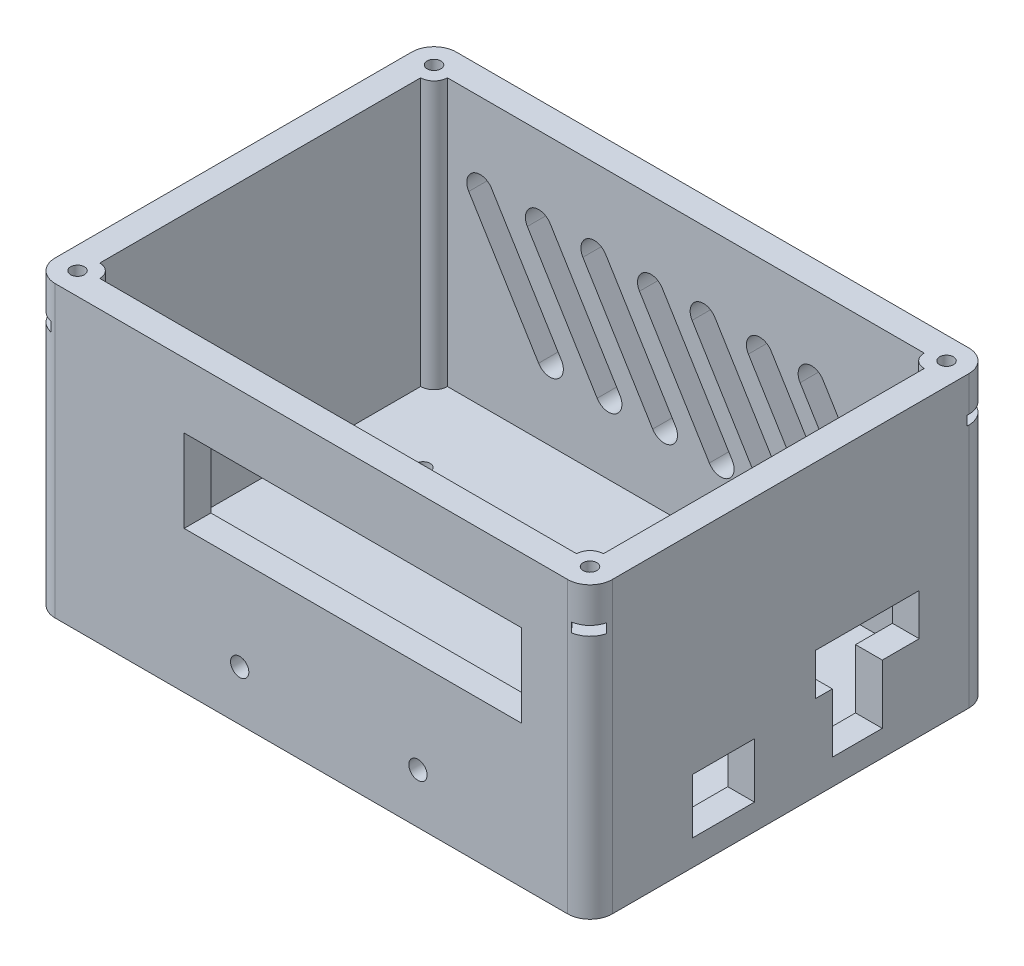
SolidWorks part; units mm, degrees
ref_plane "Front Plane" through (0, 0, 0) normal (0, 0, 1) x (1, 0, 0)
ref_plane "Top Plane" through (0, 0, 0) normal (0, 1, 0) x (1, 0, 0)
ref_plane "Right Plane" through (0, 0, 0) normal (1, 0, 0) x (0, 0, -1)
sketch "Sketch1" plane through (0, 0, 0) normal (0, 1, 0) x (1, 0, 0)
  line L0 (-62.5, 45) -> (62.5, 45)
  line L7 (62.5, 45) -> (62.5, -45)
  line L8 (-62.5, -45) -> (62.5, -45)
  line L9 (-62.5, 45) -> (-62.5, -45)
  point P1 (0, 0)
  point P2 (62.5, 0)
  dimension "D1" = 90
  dimension "D2" = 125
extrude "Boss-Extrude1" add sketch "Sketch1" along normal blind 5
sketch "Sketch2" plane through (0, 5, 0) normal (0, 1, 0) x (1, 0, 0)
  line L8 (-57.5, 40) -> (-57.5, -40)
  line L9 (-57.5, -40) -> (57.5, -40)
  line L10 (57.5, -40) -> (57.5, 40)
  line L11 (57.5, 40) -> (-57.5, 40)
  line L12 (-57.5, 40) -> (-57.5, -40)
  line L13 (-57.5, -40) -> (57.5, -40)
  line L14 (57.5, -40) -> (57.5, 40)
  line L15 (57.5, 40) -> (-57.5, 40)
  dimension "D1" = 5
extrude "Extrude-Thin1" add sketch "Sketch2" along normal blind 60 thin
fillet "Fillet1" radius 5 4 edges at (-62.5, 32.5, -45) (62.5, 32.5, -45) (62.5, 32.5, 45) (-62.5, 32.5, 45)
sketch "Sketch14" plane through (0, 0, 45) normal (0, 0, 1) x (1, 0, 0)
  line L1 (-28.5737, 50.4382) -> (47.1628, 50.4382)
  line L2 (-28.5737, 50.4382) -> (-28.5737, 31.8876)
  line L3 (-28.5737, 31.8876) -> (47.1628, 31.8876)
  line L4 (47.1628, 50.4382) -> (47.1628, 31.8876)
sketch "Sketch17" plane through (0, 0, 39) normal (0, 0, -1) x (-1, 0, 0)
  line L0 (-23.8948, 11.2058) -> (16.1052, 11.2058) construction
  circle A0 centre (-23.8948, 11.2058) radius 2.05
  circle A1 centre (16.1052, 11.2058) radius 2.05
  dimension "D2" = 4.1
  dimension "D3" = 4.1
  dimension "D1" = 40
extrude "Cut-Extrude12" cut sketch "Sketch17" against normal up to next
sketch "Sketch18" plane through (0, 0, 39) normal (0, 0, -1) x (-1, 0, 0)
  line L1 (-21.9213, 7.5472) -> (-19.7396, 11.0856)
  line L2 (-19.7396, 11.0856) -> (-21.7131, 14.7442)
  line L3 (-21.7131, 14.7442) -> (-25.8683, 14.8644)
  line L4 (-25.8683, 14.8644) -> (-28.05, 11.326)
  line L5 (-28.05, 11.326) -> (-26.0765, 7.6674)
  line L6 (-26.0765, 7.6674) -> (-21.9213, 7.5472)
  line L7 (18.0787, 7.5472) -> (20.2604, 11.0856)
  line L8 (20.2604, 11.0856) -> (18.2869, 14.7442)
  line L9 (18.2869, 14.7442) -> (14.1317, 14.8644)
  line L10 (14.1317, 14.8644) -> (11.95, 11.326)
  line L11 (11.95, 11.326) -> (13.9235, 7.6674)
  line L12 (13.9235, 7.6674) -> (18.0787, 7.5472)
  circle A0 centre (-23.8948, 11.2058) radius 3.6 construction
  circle A1 centre (16.1052, 11.2058) radius 3.6 construction
  dimension "D1" = 7.2
  dimension "D2" = 7.2
extrude "Cut-Extrude13" cut sketch "Sketch18" against normal blind 3
extrude "Cut-Extrude15" cut sketch "Sketch14" against normal up to next contours L1 L4 L3 L2
sketch "Sketch20" plane through (0, 5, 0) normal (0, 1, 0) x (1, 0, 0)
  circle A0 centre (-56.5, -39) radius 3
  circle A1 centre (-56.5, 39) radius 3
  circle A2 centre (56.5, 39) radius 3
  circle A3 centre (56.5, -39) radius 3
  dimension "D1" = 6
  dimension "D2" = 6
extrude "Boss-Extrude2" add sketch "Sketch20" along normal blind 60
sketch "Sketch21" plane through (0, 65, 0) normal (0, 1, 0) x (1, 0, 0)
  circle A0 centre (-57.5, -40) radius 1.55
  circle A1 centre (-57.5, 40) radius 1.55
  circle A2 centre (57.5, 40) radius 1.55
  circle A3 centre (57.5, -40) radius 1.55
  dimension "D1" = 3.1
extrude "Cut-Extrude16" cut sketch "Sketch21" against normal blind 15
ref_plane "Plane3" through (0, 55, 0) normal (0, 1, 0) x (1, 0, 0)
sketch "Sketch22" plane through (0, 55, 0) normal (0, 1, 0) x (1, 0, 0)
  line L0 (-56.8583, 43.1688) -> (-60.3698, 46.2698)
  line L1 (-60.5651, 38.9713) -> (-58.1417, 36.8312)
  line L2 (-58.1417, 36.8312) -> (-55.0765, 37.8599)
  line L3 (-55.0765, 37.8599) -> (-54.4349, 41.0287)
  line L4 (-54.4349, 41.0287) -> (-56.8583, 43.1688)
  line L7 (57.5, 43.2332) -> (54.7, 41.6166)
  line L8 (54.7, 41.6166) -> (54.7, 38.3834)
  line L9 (54.7, 38.3834) -> (57.5, 36.7668)
  line L10 (57.5, 36.7668) -> (60.3, 38.3834)
  line L15 (60.6503, -39.2728) -> (58.4454, -36.9082)
  line L16 (58.4454, -36.9082) -> (55.2951, -37.6353)
  line L17 (55.2951, -37.6353) -> (54.3497, -40.7272)
  line L18 (54.3497, -40.7272) -> (56.5546, -43.0918)
  line L19 (-54.3782, -40.8414) -> (-55.2104, -37.7172)
  line L20 (-55.2104, -37.7172) -> (-58.3322, -36.8758)
  line L21 (-58.3322, -36.8758) -> (-60.6218, -39.1586)
  line L24 (-56.6678, -43.1242) -> (-54.3782, -40.8414)
  line L25 (-60.3698, 46.2698) -> (-64.0167, 42.1401)
  line L26 (-64.0167, 42.1401) -> (-60.5651, 38.9713)
  line L27 (57.5, 43.2332) -> (61.574, 45.5853)
  line L28 (61.574, 45.5853) -> (64.3757, 40.7325)
  line L29 (64.3757, 40.7325) -> (60.3, 38.3834)
  line L30 (56.5546, -43.0918) -> (59.7049, -46.4705)
  line L31 (59.7049, -46.4705) -> (63.7747, -42.6756)
  line L32 (63.7747, -42.6756) -> (60.6503, -39.2728)
  line L33 (-60.6218, -39.1586) -> (-64.278, -42.804)
  line L34 (-64.278, -42.804) -> (-60.3698, -46.7238)
  line L36 (-56.6678, -43.1242) -> (-60.3698, -46.7238)
  line L38 (-60.2057, -40.7207) -> (-59.7896, -42.2828) [skipped]
  line L39 (-59.7896, -42.2828) -> (-58.2287, -42.7035) [skipped]
  line L40 (58.1297, -42.7283) -> (59.7049, -42.3647) [skipped]
  line L41 (60.1776, -40.8188) -> (60.6503, -39.2728) [skipped]
  line L42 (60.3, 41.6166) -> (58.9, 42.4249) [skipped]
  line L43 (60.3, 38.3834) -> (60.3, 40) [skipped]
  line L44 (-56.8583, 43.1688) -> (-58.3909, 42.6545) [skipped]
  line L45 (-60.2443, 40.5557) -> (-60.5651, 38.9713) [skipped]
  circle A0 centre (-57.5, 40) radius 2.8 construction
  circle A1 centre (57.5, 40) radius 2.8 construction
  circle A2 centre (57.5, -40) radius 2.8 construction
  circle A3 centre (-57.5, -40) radius 2.8 construction
  dimension "D2" = 5.6
  dimension "D3" = 5.6
  dimension "D4" = 5.6
extrude "Cut-Extrude17" cut sketch "Sketch22" along normal blind 2.1
sketch "Sketch23" plane through (0, 0, -45) normal (0, 0, -1) x (-1, 0, 0)
  line L0 (-38.1886, 46.8799) -> (46.1005, 46.8799) construction
  line L1 (-28.2059, 46.8799) -> (-43.8731, 21.3293) construction
  line L2 (-38.1886, 21.3293) -> (46.1005, 21.3293) construction
  line L3 (-25.6484, 45.3116) -> (-41.3157, 19.7611)
  line L4 (-30.7633, 48.4481) -> (-46.4306, 22.8976)
  line L5 (-16.5954, 46.643) -> (-32.2626, 21.0925) construction
  line L10 (-14.0379, 45.0748) -> (-29.7052, 19.5243)
  line L15 (-19.1528, 48.2112) -> (-34.8201, 22.6607)
  line L18 (-3.967, 46.8799) -> (-19.6342, 21.3293) construction
  line L21 (-1.4095, 45.3116) -> (-17.0768, 19.7611)
  line L24 (-6.5244, 48.4481) -> (-22.1917, 22.8976)
  line L25 (7.8336, 46.643) -> (-7.8336, 21.0925) construction
  line L26 (10.3911, 45.0748) -> (-5.2762, 19.5243)
  line L27 (5.2762, 48.2112) -> (-10.3911, 22.6607)
  line L28 (20.5417, 46.8799) -> (4.8744, 21.3293) construction
  line L29 (23.0992, 45.3116) -> (7.4319, 19.7611)
  line L30 (17.9842, 48.4481) -> (2.3169, 22.8976)
  line L31 (33.0039, 46.643) -> (17.3366, 21.0925) construction
  line L32 (35.5614, 45.0748) -> (19.8941, 19.5243)
  line L33 (30.4464, 48.2112) -> (14.7791, 22.6607)
  line L34 (46.1447, 46.8799) -> (30.4774, 21.3293) construction
  line L35 (48.7022, 45.3116) -> (33.0349, 19.7611)
  line L36 (43.5872, 48.4481) -> (27.92, 22.8976)
  arc A0 (-25.6484, 45.3116) -> (-30.7633, 48.4481) centre (-28.2059, 46.8799) ccw
  arc A1 (-46.4306, 22.8976) -> (-41.3157, 19.7611) centre (-43.8731, 21.3293) ccw
  arc A16 (-14.0379, 45.0748) -> (-19.1528, 48.2112) centre (-16.5954, 46.643) ccw
  arc A17 (-34.8201, 22.6607) -> (-29.7052, 19.5243) centre (-32.2626, 21.0925) ccw
  arc A18 (-1.4095, 45.3116) -> (-6.5244, 48.4481) centre (-3.967, 46.8799) ccw
  arc A19 (-22.1917, 22.8976) -> (-17.0768, 19.7611) centre (-19.6342, 21.3293) ccw
  arc A20 (10.3911, 45.0748) -> (5.2762, 48.2112) centre (7.8336, 46.643) ccw
  arc A21 (-10.3911, 22.6607) -> (-5.2762, 19.5243) centre (-7.8336, 21.0925) ccw
  arc A22 (23.0992, 45.3116) -> (17.9842, 48.4481) centre (20.5417, 46.8799) ccw
  arc A23 (2.3169, 22.8976) -> (7.4319, 19.7611) centre (4.8744, 21.3293) ccw
  arc A24 (35.5614, 45.0748) -> (30.4464, 48.2112) centre (33.0039, 46.643) ccw
  arc A25 (14.7791, 22.6607) -> (19.8941, 19.5243) centre (17.3366, 21.0925) ccw
  arc A26 (48.7022, 45.3116) -> (43.5872, 48.4481) centre (46.1447, 46.8799) ccw
  arc A27 (27.92, 22.8976) -> (33.0349, 19.7611) centre (30.4774, 21.3293) ccw
  point P6 (-36.0395, 34.1046)
  point P14 (-11.8006, 34.1046)
  point P19 (-24.429, 33.8677)
  point P28 (0, 33.8677)
  point P35 (12.7081, 34.1046)
  point P42 (25.1703, 33.8677)
  point P49 (38.3111, 34.1046)
extrude "Cut-Extrude18" cut sketch "Sketch23" against normal up to next
sketch "Sketch26" plane through (62.5, 0, 0) normal (1, 0, 0) x (0, 0, -1)
  line L0 (5.5789, 19.0474) -> (9.3821, 19.0474)
  line L1 (5.5789, 28.4195) -> (28.8734, 28.4195)
  line L2 (5.5789, 28.4195) -> (5.5789, 19.0474)
  line L4 (28.8734, 28.4195) -> (28.8734, 19.0474)
  line L6 (9.3821, 19.0474) -> (9.3821, 5.7756)
  line L7 (9.3821, 5.7756) -> (20.5879, 5.7756)
  line L8 (20.5879, 19.0474) -> (20.5879, 5.7756)
  line L9 (-21.9936, 18.1088) -> (-8.0881, 18.1088)
  line L10 (-21.9936, 18.1088) -> (-21.9936, 5.7756)
  line L11 (-21.9936, 5.7756) -> (-8.0881, 5.7756)
  line L12 (-8.0881, 18.1088) -> (-8.0881, 5.7756)
  line L13 (20.5879, 19.0474) -> (28.8734, 19.0474)
extrude "Cut-Extrude19" cut sketch "Sketch26" against normal up to next
sketch "Sketch27" plane through (0, 5, 0) normal (0, 1, 0) x (1, 0, 0)
  circle A0 centre (42.0461, 20.5403) radius 1.5875
  circle A1 centre (40.7761, -27.7197) radius 1.5875
  circle A2 centre (-40.5039, 20.5403) radius 1.5875
  circle A3 centre (-34.1539, -27.7197) radius 1.5875
extrude "Cut-Extrude20" cut sketch "Sketch27" against normal up to next
